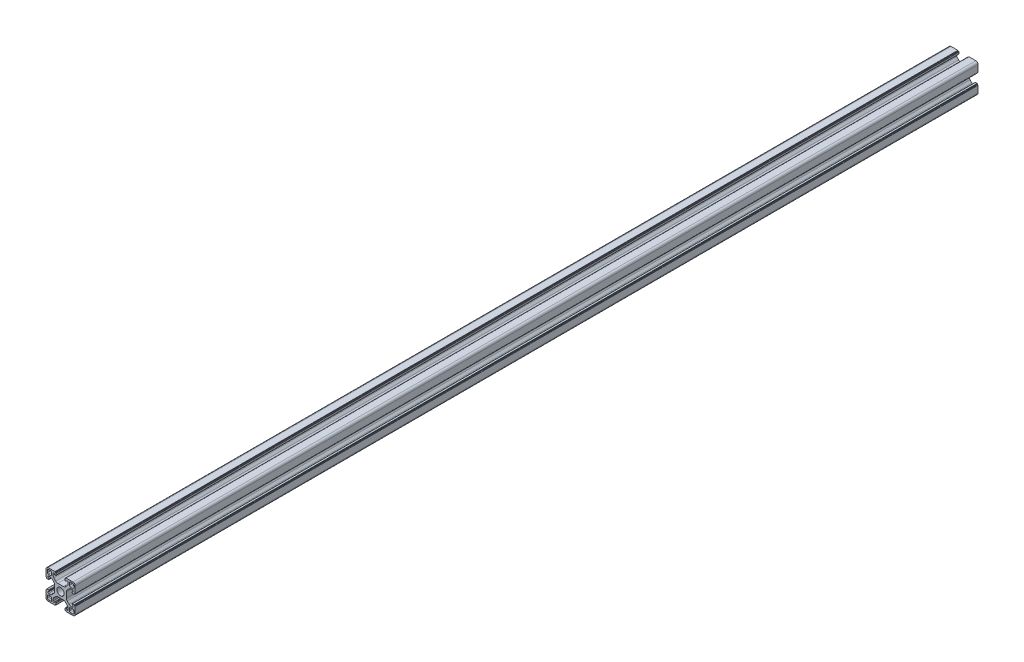
SolidWorks part; units mm, degrees
material "1060 Сплав"
ref_plane "Спереди" through (0, 0, 0) normal (0, 0, 1) x (1, 0, 0)
ref_plane "Сверху" through (0, 0, 0) normal (0, 1, 0) x (1, 0, 0)
ref_plane "Справа" through (0, 0, 0) normal (1, 0, 0) x (0, 0, -1)
sketch "Эскиз1" plane through (0, 0, 0) normal (0, 0, 1) x (1, 0, 0)
  line L0 (-22.0052, 70.3096) -> (-25.0052, 67.3096) construction
  line L1 (-31.1052, 65.2096) -> (-29.2064, 65.2096)
  line L2 (-31.1052, 61.2096) -> (-21.1052, 71.2096) construction
  line L3 (-23.5052, 68.8096) -> (-25.0052, 70.3096) construction
  line L4 (-27.7922, 65.7954) -> (-26.4909, 67.0967)
  line L5 (-24.2052, 67.3096) -> (-22.8052, 67.3096)
  line L6 (-25.0052, 68.1096) -> (-25.0052, 69.5096)
  line L7 (-22.8052, 70.3096) -> (-24.2052, 70.3096)
  line L8 (-25.9052, 69.4096) -> (-25.9052, 68.5109)
  line L9 (-27.3419, 69.2829) -> (-26.8616, 69.7632)
  line L10 (-27.9052, 70.7587) -> (-27.4052, 70.7587)
  line L11 (-27.5187, 69.2096) -> (-27.8052, 69.2096)
  line L12 (-26.508, 69.9096) -> (-26.4052, 69.9096)
  line L13 (-27.4052, 71.0596) -> (-27.4052, 70.7587)
  line L14 (-28.0552, 70.6087) -> (-28.0552, 69.4596)
  line L15 (-22.6052, 71.2096) -> (-27.2552, 71.2096)
  line L16 (-22.0052, 69.5096) -> (-22.0052, 68.1096)
  line L17 (-21.1052, 69.7096) -> (-21.1052, 65.0596)
  line L18 (-21.7061, 64.2596) -> (-22.8552, 64.2596)
  line L19 (-21.2552, 64.9096) -> (-21.5561, 64.9096)
  line L20 (-22.4052, 65.8068) -> (-22.4052, 65.9096)
  line L21 (-23.1052, 64.7961) -> (-23.1052, 64.5096)
  line L22 (-21.5561, 64.4096) -> (-21.5561, 64.9096)
  line L23 (-23.0319, 64.9729) -> (-22.5516, 65.4532)
  line L24 (-22.9052, 66.4096) -> (-23.8039, 66.4096)
  line L25 (-26.5194, 64.5226) -> (-25.2181, 65.8239)
  line L26 (-27.1052, 61.2096) -> (-27.1052, 63.1084)
  line L27 (-27.1052, 61.2096) -> (-27.1052, 59.3109)
  line L28 (-26.5194, 57.8967) -> (-25.2181, 56.5954)
  line L29 (-25.0052, 54.3096) -> (-25.0052, 52.9096)
  line L30 (-24.2052, 55.1096) -> (-22.8052, 55.1096)
  line L31 (-22.0052, 52.9096) -> (-22.0052, 54.3096)
  line L32 (-22.9052, 56.0096) -> (-23.8039, 56.0096)
  line L33 (-23.0319, 57.4464) -> (-22.5516, 56.9661)
  line L34 (-21.5561, 58.0096) -> (-21.5561, 57.5096)
  line L35 (-23.1052, 57.6232) -> (-23.1052, 57.9096)
  line L36 (-22.4052, 56.6125) -> (-22.4052, 56.5096)
  line L37 (-21.2552, 57.5096) -> (-21.5561, 57.5096)
  line L38 (-21.7061, 58.1596) -> (-22.8552, 58.1596)
  line L39 (-21.1052, 52.7096) -> (-21.1052, 57.3596)
  line L40 (-22.8052, 52.1096) -> (-24.2052, 52.1096)
  line L41 (-22.6052, 51.2096) -> (-27.2552, 51.2096)
  line L42 (-28.0552, 51.8106) -> (-28.0552, 52.9596)
  line L43 (-27.4052, 51.3596) -> (-27.4052, 51.6606)
  line L44 (-26.508, 52.5096) -> (-26.4052, 52.5096)
  line L45 (-27.5187, 53.2096) -> (-27.8052, 53.2096)
  line L46 (-27.9052, 51.6606) -> (-27.4052, 51.6606)
  line L47 (-27.3419, 53.1364) -> (-26.8616, 52.6561)
  line L48 (-25.9052, 53.0096) -> (-25.9052, 53.9084)
  line L49 (-27.7922, 56.6239) -> (-26.4909, 55.3226)
  line L50 (-31.1052, 57.2096) -> (-29.2064, 57.2096)
  line L51 (-22.0052, 52.1096) -> (-25.0052, 55.1096) construction
  line L52 (-31.1052, 61.2096) -> (-21.1052, 51.2096) construction
  line L53 (-23.5052, 53.6096) -> (-22.0052, 55.1096) construction
  line L54 (-31.1052, 57.2096) -> (-33.0039, 57.2096)
  line L55 (-34.4181, 56.6239) -> (-35.7194, 55.3226)
  line L56 (-38.0052, 55.1096) -> (-39.4052, 55.1096)
  line L57 (-37.2052, 54.3096) -> (-37.2052, 52.9096)
  line L58 (-39.4052, 52.1096) -> (-38.0052, 52.1096)
  line L59 (-36.3052, 53.0096) -> (-36.3052, 53.9084)
  line L60 (-34.8684, 53.1364) -> (-35.3487, 52.6561)
  line L61 (-34.3052, 51.6606) -> (-34.8052, 51.6606)
  line L62 (-34.6916, 53.2096) -> (-34.4052, 53.2096)
  line L63 (-35.7023, 52.5096) -> (-35.8052, 52.5096)
  line L64 (-34.8052, 51.3596) -> (-34.8052, 51.6606)
  line L65 (-34.1552, 51.8106) -> (-34.1552, 52.9596)
  line L66 (-39.6052, 51.2096) -> (-34.9552, 51.2096)
  line L67 (-40.2052, 52.9096) -> (-40.2052, 54.3096)
  line L68 (-41.1052, 52.7096) -> (-41.1052, 57.3596)
  line L69 (-40.5042, 58.1596) -> (-39.3552, 58.1596)
  line L70 (-40.9552, 57.5096) -> (-40.6542, 57.5096)
  line L71 (-39.8052, 56.6125) -> (-39.8052, 56.5096)
  line L72 (-39.1052, 57.6232) -> (-39.1052, 57.9096)
  line L73 (-40.6542, 58.0096) -> (-40.6542, 57.5096)
  line L74 (-39.1784, 57.4464) -> (-39.6587, 56.9661)
  line L75 (-39.3052, 56.0096) -> (-38.4064, 56.0096)
  line L76 (-35.6909, 57.8967) -> (-36.9922, 56.5954)
  line L77 (-35.1052, 61.2096) -> (-35.1052, 59.3109)
  line L78 (-40.2052, 52.1096) -> (-37.2052, 55.1096) construction
  line L79 (-31.1052, 61.2096) -> (-41.1052, 51.2096) construction
  line L80 (-38.7052, 53.6096) -> (-37.2052, 52.1096) construction
  line L81 (-35.1052, 61.2096) -> (-35.1052, 63.1084)
  line L82 (-35.6909, 64.5226) -> (-36.9922, 65.8239)
  line L83 (-37.2052, 68.1096) -> (-37.2052, 69.5096)
  line L84 (-38.0052, 67.3096) -> (-39.4052, 67.3096)
  line L85 (-40.2052, 69.5096) -> (-40.2052, 68.1096)
  line L86 (-39.3052, 66.4096) -> (-38.4064, 66.4096)
  line L87 (-39.1784, 64.9729) -> (-39.6587, 65.4532)
  line L88 (-40.6542, 64.4096) -> (-40.6542, 64.9096)
  line L89 (-39.1052, 64.7961) -> (-39.1052, 64.5096)
  line L90 (-39.8052, 65.8068) -> (-39.8052, 65.9096)
  line L91 (-40.9552, 64.9096) -> (-40.6542, 64.9096)
  line L92 (-40.5042, 64.2596) -> (-39.3552, 64.2596)
  line L93 (-41.1052, 69.7096) -> (-41.1052, 65.0596)
  line L94 (-39.4052, 70.3096) -> (-38.0052, 70.3096)
  line L95 (-39.6052, 71.2096) -> (-34.9552, 71.2096)
  line L96 (-34.1552, 70.6087) -> (-34.1552, 69.4596)
  line L97 (-34.8052, 71.0596) -> (-34.8052, 70.7587)
  line L98 (-35.7023, 69.9096) -> (-35.8052, 69.9096)
  line L99 (-34.6916, 69.2096) -> (-34.4052, 69.2096)
  line L100 (-34.3052, 70.7587) -> (-34.8052, 70.7587)
  line L101 (-34.8684, 69.2829) -> (-35.3487, 69.7632)
  line L102 (-36.3052, 69.4096) -> (-36.3052, 68.5109)
  line L103 (-34.4181, 65.7954) -> (-35.7194, 67.0967)
  line L104 (-31.1052, 65.2096) -> (-33.0039, 65.2096)
  line L105 (-42.8692, 61.2096) -> (-19.6008, 61.2096) construction
  line L106 (-40.2052, 70.3096) -> (-37.2052, 67.3096) construction
  line L107 (-31.1052, 49.1232) -> (-31.1052, 71.9286) construction
  line L108 (-31.1052, 61.2096) -> (-41.1052, 71.2096) construction
  line L109 (-38.7052, 68.8096) -> (-40.2052, 67.3096) construction
  arc A0 (-22.0052, 69.5096) -> (-22.8052, 70.3096) centre (-22.8052, 69.5096) ccw
  arc A1 (-24.2052, 70.3096) -> (-25.0052, 69.5096) centre (-24.2052, 69.5096) ccw
  arc A2 (-24.2052, 67.3096) -> (-25.0052, 68.1096) centre (-24.2052, 68.1096) cw
  arc A3 (-22.6052, 71.2096) -> (-21.1052, 69.7096) centre (-22.6052, 69.7096) cw
  arc A4 (-27.9052, 70.7587) -> (-28.0552, 70.6087) centre (-27.9052, 70.6087) ccw
  arc A5 (-27.2552, 71.2096) -> (-27.4052, 71.0596) centre (-27.2552, 71.0596) ccw
  arc A6 (-27.5187, 69.2096) -> (-27.3419, 69.2829) centre (-27.5187, 69.4596) ccw
  arc A7 (-27.8052, 69.2096) -> (-28.0552, 69.4596) centre (-27.8052, 69.4596) cw
  arc A8 (-26.8616, 69.7632) -> (-26.508, 69.9096) centre (-26.508, 69.4096) cw
  arc A9 (-26.4052, 69.9096) -> (-25.9052, 69.4096) centre (-26.4052, 69.4096) cw
  arc A10 (-28.6052, 61.2096) -> (-31.1052, 63.7096) centre (-31.1052, 61.2096) ccw
  arc A11 (-29.2064, 65.2096) -> (-27.7922, 65.7954) centre (-29.2064, 67.2096) ccw
  arc A12 (-25.9052, 68.5109) -> (-26.4909, 67.0967) centre (-27.9052, 68.5109) cw
  arc A13 (-22.0052, 68.1096) -> (-22.8052, 67.3096) centre (-22.8052, 68.1096) cw
  arc A14 (-22.4052, 65.9096) -> (-22.9052, 66.4096) centre (-22.9052, 65.9096) ccw
  arc A15 (-22.5516, 65.4532) -> (-22.4052, 65.8068) centre (-22.9052, 65.8068) ccw
  arc A16 (-23.1052, 64.5096) -> (-22.8552, 64.2596) centre (-22.8552, 64.5096) ccw
  arc A17 (-23.1052, 64.7961) -> (-23.0319, 64.9729) centre (-22.8552, 64.7961) cw
  arc A18 (-21.1052, 65.0596) -> (-21.2552, 64.9096) centre (-21.2552, 65.0596) cw
  arc A19 (-21.5561, 64.4096) -> (-21.7061, 64.2596) centre (-21.7061, 64.4096) cw
  arc A20 (-23.8039, 66.4096) -> (-25.2181, 65.8239) centre (-23.8039, 64.4096) ccw
  arc A21 (-27.1052, 63.1084) -> (-26.5194, 64.5226) centre (-25.1052, 63.1084) cw
  arc A22 (-22.8052, 52.1096) -> (-22.0052, 52.9096) centre (-22.8052, 52.9096) ccw
  arc A23 (-22.0052, 54.3096) -> (-22.8052, 55.1096) centre (-22.8052, 54.3096) ccw
  arc A24 (-25.0052, 54.3096) -> (-24.2052, 55.1096) centre (-24.2052, 54.3096) cw
  arc A25 (-21.1052, 52.7096) -> (-22.6052, 51.2096) centre (-22.6052, 52.7096) cw
  arc A26 (-21.5561, 58.0096) -> (-21.7061, 58.1596) centre (-21.7061, 58.0096) ccw
  arc A27 (-21.1052, 57.3596) -> (-21.2552, 57.5096) centre (-21.2552, 57.3596) ccw
  arc A28 (-23.1052, 57.6232) -> (-23.0319, 57.4464) centre (-22.8552, 57.6232) ccw
  arc A29 (-23.1052, 57.9096) -> (-22.8552, 58.1596) centre (-22.8552, 57.9096) cw
  arc A30 (-22.5516, 56.9661) -> (-22.4052, 56.6125) centre (-22.9052, 56.6125) cw
  arc A31 (-22.4052, 56.5096) -> (-22.9052, 56.0096) centre (-22.9052, 56.5096) cw
  arc A32 (-31.1052, 58.7096) -> (-28.6052, 61.2096) centre (-31.1052, 61.2096) ccw
  arc A33 (-27.1052, 59.3109) -> (-26.5194, 57.8967) centre (-25.1052, 59.3109) ccw
  arc A34 (-23.8039, 56.0096) -> (-25.2181, 56.5954) centre (-23.8039, 58.0096) cw
  arc A35 (-24.2052, 52.1096) -> (-25.0052, 52.9096) centre (-24.2052, 52.9096) cw
  arc A36 (-26.4052, 52.5096) -> (-25.9052, 53.0096) centre (-26.4052, 53.0096) ccw
  arc A37 (-26.8616, 52.6561) -> (-26.508, 52.5096) centre (-26.508, 53.0096) ccw
  arc A38 (-27.8052, 53.2096) -> (-28.0552, 52.9596) centre (-27.8052, 52.9596) ccw
  arc A39 (-27.5187, 53.2096) -> (-27.3419, 53.1364) centre (-27.5187, 52.9596) cw
  arc A40 (-27.2552, 51.2096) -> (-27.4052, 51.3596) centre (-27.2552, 51.3596) cw
  arc A41 (-27.9052, 51.6606) -> (-28.0552, 51.8106) centre (-27.9052, 51.8106) cw
  arc A42 (-25.9052, 53.9084) -> (-26.4909, 55.3226) centre (-27.9052, 53.9084) ccw
  arc A43 (-29.2064, 57.2096) -> (-27.7922, 56.6239) centre (-29.2064, 55.2096) cw
  arc A44 (-40.2052, 52.9096) -> (-39.4052, 52.1096) centre (-39.4052, 52.9096) ccw
  arc A45 (-38.0052, 52.1096) -> (-37.2052, 52.9096) centre (-38.0052, 52.9096) ccw
  arc A46 (-38.0052, 55.1096) -> (-37.2052, 54.3096) centre (-38.0052, 54.3096) cw
  arc A47 (-39.6052, 51.2096) -> (-41.1052, 52.7096) centre (-39.6052, 52.7096) cw
  arc A48 (-34.3052, 51.6606) -> (-34.1552, 51.8106) centre (-34.3052, 51.8106) ccw
  arc A49 (-34.9552, 51.2096) -> (-34.8052, 51.3596) centre (-34.9552, 51.3596) ccw
  arc A50 (-34.6916, 53.2096) -> (-34.8684, 53.1364) centre (-34.6916, 52.9596) ccw
  arc A51 (-34.4052, 53.2096) -> (-34.1552, 52.9596) centre (-34.4052, 52.9596) cw
  arc A52 (-35.3487, 52.6561) -> (-35.7023, 52.5096) centre (-35.7023, 53.0096) cw
  arc A53 (-35.8052, 52.5096) -> (-36.3052, 53.0096) centre (-35.8052, 53.0096) cw
  arc A54 (-33.6052, 61.2096) -> (-31.1052, 58.7096) centre (-31.1052, 61.2096) ccw
  arc A55 (-33.0039, 57.2096) -> (-34.4181, 56.6239) centre (-33.0039, 55.2096) ccw
  arc A56 (-36.3052, 53.9084) -> (-35.7194, 55.3226) centre (-34.3052, 53.9084) cw
  arc A57 (-40.2052, 54.3096) -> (-39.4052, 55.1096) centre (-39.4052, 54.3096) cw
  arc A58 (-39.8052, 56.5096) -> (-39.3052, 56.0096) centre (-39.3052, 56.5096) ccw
  arc A59 (-39.6587, 56.9661) -> (-39.8052, 56.6125) centre (-39.3052, 56.6125) ccw
  arc A60 (-39.1052, 57.9096) -> (-39.3552, 58.1596) centre (-39.3552, 57.9096) ccw
  arc A61 (-39.1052, 57.6232) -> (-39.1784, 57.4464) centre (-39.3552, 57.6232) cw
  arc A62 (-41.1052, 57.3596) -> (-40.9552, 57.5096) centre (-40.9552, 57.3596) cw
  arc A63 (-40.6542, 58.0096) -> (-40.5042, 58.1596) centre (-40.5042, 58.0096) cw
  arc A64 (-38.4064, 56.0096) -> (-36.9922, 56.5954) centre (-38.4064, 58.0096) ccw
  arc A65 (-35.1052, 59.3109) -> (-35.6909, 57.8967) centre (-37.1052, 59.3109) cw
  arc A66 (-39.4052, 70.3096) -> (-40.2052, 69.5096) centre (-39.4052, 69.5096) ccw
  arc A67 (-40.2052, 68.1096) -> (-39.4052, 67.3096) centre (-39.4052, 68.1096) ccw
  arc A68 (-37.2052, 68.1096) -> (-38.0052, 67.3096) centre (-38.0052, 68.1096) cw
  arc A69 (-41.1052, 69.7096) -> (-39.6052, 71.2096) centre (-39.6052, 69.7096) cw
  arc A70 (-40.6542, 64.4096) -> (-40.5042, 64.2596) centre (-40.5042, 64.4096) ccw
  arc A71 (-41.1052, 65.0596) -> (-40.9552, 64.9096) centre (-40.9552, 65.0596) ccw
  arc A72 (-39.1052, 64.7961) -> (-39.1784, 64.9729) centre (-39.3552, 64.7961) ccw
  arc A73 (-39.1052, 64.5096) -> (-39.3552, 64.2596) centre (-39.3552, 64.5096) cw
  arc A74 (-39.6587, 65.4532) -> (-39.8052, 65.8068) centre (-39.3052, 65.8068) cw
  arc A75 (-39.8052, 65.9096) -> (-39.3052, 66.4096) centre (-39.3052, 65.9096) cw
  arc A76 (-31.1052, 63.7096) -> (-33.6052, 61.2096) centre (-31.1052, 61.2096) ccw
  arc A77 (-35.1052, 63.1084) -> (-35.6909, 64.5226) centre (-37.1052, 63.1084) ccw
  arc A78 (-38.4064, 66.4096) -> (-36.9922, 65.8239) centre (-38.4064, 64.4096) cw
  arc A79 (-38.0052, 70.3096) -> (-37.2052, 69.5096) centre (-38.0052, 69.5096) cw
  arc A80 (-35.8052, 69.9096) -> (-36.3052, 69.4096) centre (-35.8052, 69.4096) ccw
  arc A81 (-35.3487, 69.7632) -> (-35.7023, 69.9096) centre (-35.7023, 69.4096) ccw
  arc A82 (-34.4052, 69.2096) -> (-34.1552, 69.4596) centre (-34.4052, 69.4596) ccw
  arc A83 (-34.6916, 69.2096) -> (-34.8684, 69.2829) centre (-34.6916, 69.4596) cw
  arc A84 (-34.9552, 71.2096) -> (-34.8052, 71.0596) centre (-34.9552, 71.0596) cw
  arc A85 (-34.3052, 70.7587) -> (-34.1552, 70.6087) centre (-34.3052, 70.6087) cw
  arc A86 (-36.3052, 68.5109) -> (-35.7194, 67.0967) centre (-34.3052, 68.5109) ccw
  arc A87 (-33.0039, 65.2096) -> (-34.4181, 65.7954) centre (-33.0039, 67.2096) cw
  point P0 (-31.1052, 61.2096)
  point P9 (-31.1052, 61.2096)
  point P40 (-22.4052, 64.9096)
  point P93 (-27.4052, 52.5096)
  point P144 (-27.4052, 69.9096)
  point P152 (-22.4052, 57.5096)
  point P153 (-31.1052, 57.2854)
  point P154 (-31.1052, 61.2096)
  point P189 (-39.8052, 57.5096)
  point P228 (-34.8052, 52.5096)
  point P229 (-35.0294, 61.2096)
  point P230 (-31.1052, 61.2096)
  point P268 (-34.8052, 69.9096)
  point P273 (-27.1809, 61.2096)
  point P306 (-39.8052, 64.9096)
  point P307 (-31.1052, 65.1339)
  point P309 (-31.1052, 61.2096)
  dimension "D3" = 5
  dimension "D6" = 2
  dimension "D1" = 2
  dimension "D2" = 6
  dimension "D4" = 4
  dimension "D5" = 0.9
extrude "Бобышка-Вытянуть1" add sketch "Эскиз1" along normal blind 620
